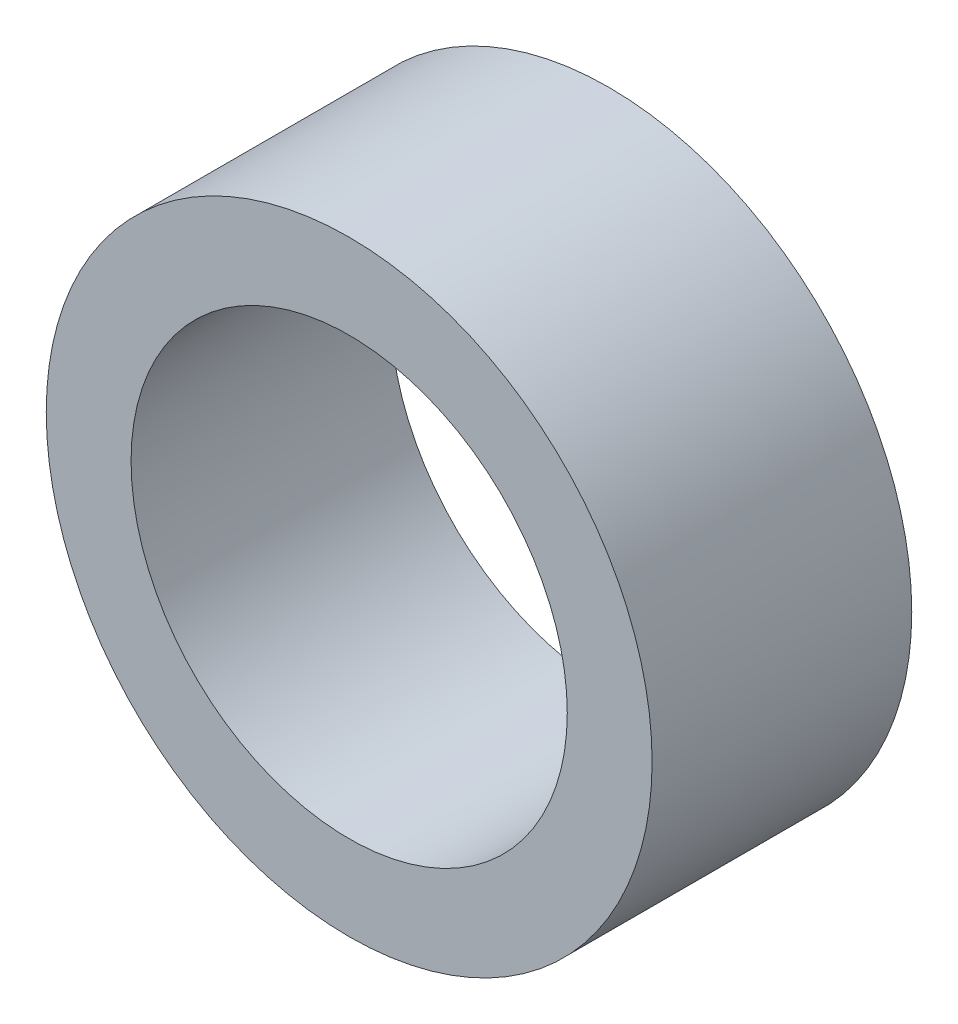
SolidWorks part; units mm, degrees
material "聚脂树脂"
ref_plane "前视基准面" through (0, 0, 0) normal (0, 0, 1) x (1, 0, 0)
ref_plane "上视基准面" through (0, 0, 0) normal (0, 1, 0) x (1, 0, 0)
ref_plane "右视基准面" through (0, 0, 0) normal (1, 0, 0) x (0, 0, -1)
sketch "草图1" plane through (0, 0, 0) normal (0, 0, 1) x (1, 0, 0)
  circle A0 centre (0, 0) radius 25.2
  circle A1 centre (0, 0) radius 35
  dimension "D1" = 70
  dimension "D2" = 50.4
extrude "凸台-拉伸1" add sketch "草图1" along normal mid plane 30
